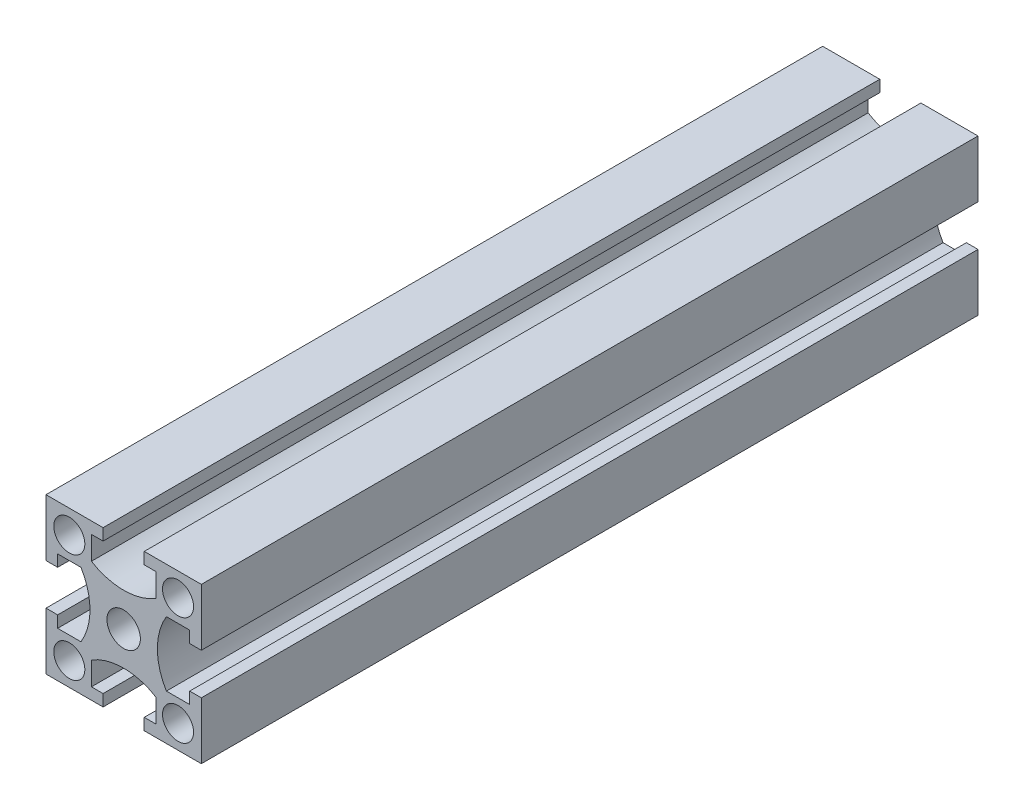
SolidWorks part; units mm, degrees
ref_plane "정면" through (0, 0, 0) normal (0, 0, 1) x (1, 0, 0)
ref_plane "윗면" through (0, 0, 0) normal (0, 1, 0) x (1, 0, 0)
ref_plane "우측면" through (0, 0, 0) normal (1, 0, 0) x (0, 0, -1)
sketch "스케치1" plane through (0, 0, 0) normal (0, 0, 1) x (1, 0, 0)
  line L1 (-10, 10) -> (10, 10)
  line L2 (-10, 10) -> (-10, -10)
  line L3 (-10, -10) -> (10, -10)
  line L4 (10, 10) -> (10, -10)
  line L5 (-10, 10) -> (10, -10) construction
  line L6 (-10, -10) -> (10, 10) construction
  point P0 (0, 0)
  dimension "D1" = 20
  dimension "D2" = 20
extrude "보스-돌출1" add sketch "스케치1" along normal blind 100
sketch "스케치2" plane through (0, 0, 100) normal (0, 0, 1) x (1, 0, 0)
  line L0 (-2.65, 10) -> (-2.65, 8.5)
  line L1 (10, 10) -> (-10, 10) construction
  line L2 (-2.65, 8.5) -> (-4.15, 8.5)
  line L3 (-4.15, 8.5) -> (-4.15, 5.5)
  line L4 (-2.65, 10) -> (2.65, 10)
  line L5 (2.65, 10) -> (2.65, 8.5)
  line L6 (2.65, 8.5) -> (4.15, 8.5)
  line L7 (4.15, 8.5) -> (4.15, 5.5)
  line L8 (10, 2.65) -> (8.5, 2.65)
  line L9 (8.5, 2.65) -> (8.5, 4.15)
  line L10 (8.5, 4.15) -> (5.5, 4.15)
  line L11 (10, 2.65) -> (10, -2.65)
  line L12 (10, -2.65) -> (8.5, -2.65)
  line L13 (8.5, -2.65) -> (8.5, -4.15)
  line L14 (8.5, -4.15) -> (5.5, -4.15)
  line L15 (2.65, -10) -> (2.65, -8.5)
  line L16 (2.65, -8.5) -> (4.15, -8.5)
  line L17 (4.15, -8.5) -> (4.15, -5.5)
  line L18 (2.65, -10) -> (-2.65, -10)
  line L19 (-2.65, -10) -> (-2.65, -8.5)
  line L20 (-2.65, -8.5) -> (-4.15, -8.5)
  line L21 (-4.15, -8.5) -> (-4.15, -5.5)
  line L22 (-10, -2.65) -> (-8.5, -2.65)
  line L23 (-8.5, -2.65) -> (-8.5, -4.15)
  line L24 (-8.5, -4.15) -> (-5.5, -4.15)
  line L25 (-10, -2.65) -> (-10, 2.65)
  line L26 (-10, 2.65) -> (-8.5, 2.65)
  line L27 (-8.5, 2.65) -> (-8.5, 4.15)
  line L28 (-8.5, 4.15) -> (-5.5, 4.15)
  arc A1 (-4.15, 5.5) -> (4.15, 5.5) centre (0, 12.3394) ccw
  arc A2 (5.5, 4.15) -> (5.5, -4.15) centre (12.3394, 0) ccw
  arc A3 (4.15, -5.5) -> (-4.15, -5.5) centre (0, -12.3394) ccw
  arc A4 (-5.5, -4.15) -> (-5.5, 4.15) centre (-12.3394, 0) ccw
  circle A5 centre (0, 0) radius 2.15
  circle A6 centre (-7, 7) radius 2
  circle A7 centre (7, 7) radius 2
  circle A8 centre (7, -7) radius 2
  circle A9 centre (-7, -7) radius 2
  point P4 (-2.65, 9.25)
  point P43 (0, 0)
  dimension "D2" = 1.5
  dimension "D8" = 4.3
  dimension "D9" = 4
  dimension "D10" = 4
  dimension "D11" = 4
  dimension "D12" = 4
  dimension "D21" = 8
  dimension "D1" = 5.3
  dimension "D3" = 8.3
  dimension "D4" = 4.15
  dimension "D5" = 2.65
  dimension "D6" = 4
  dimension "D7" = 3
  dimension "D13" = 14
  dimension "D14" = 7
  dimension "D15" = 7
  dimension "D16" = 7
  dimension "D17" = 14
  dimension "D18" = 7
  dimension "D19" = 7
  dimension "D20" = 7
extrude "컷-돌출1" cut sketch "스케치2" against normal blind 300
